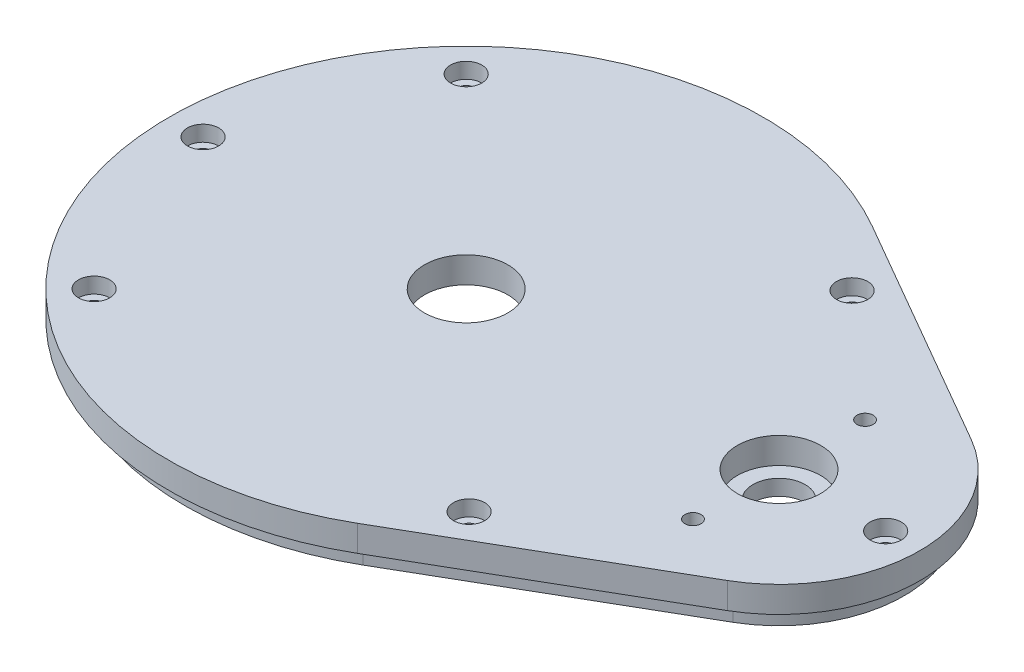
SolidWorks part; units mm, degrees
ref_plane "Front Plane" through (0, 0, 0) normal (0, 0, 1) x (1, 0, 0)
ref_plane "Top Plane" through (0, 0, 0) normal (0, 1, 0) x (1, 0, 0)
ref_plane "Right Plane" through (0, 0, 0) normal (1, 0, 0) x (0, 0, -1)
sketch "Sketch1" plane through (0, 0, 0) normal (0, 1, 0) x (1, 0, 0)
  line L8 (45, -16.5) -> (45, 16.5) construction
  line L9 (13.5, -49.3634) -> (58.5, -23.3827)
  line L10 (13.5, 49.3634) -> (58.5, 23.3827)
  circle A0 centre (-15, 0) radius 46.5 construction
  circle A1 centre (45, 0) radius 16.5 construction
  circle A2 centre (-15, 0) radius 8
  circle A3 centre (45, 0) radius 8
  circle A4 centre (45, 16.5) radius 1.55
  circle A5 centre (45, -16.5) radius 1.55
  circle A8 centre (-15, 0) radius 57 construction
  circle A9 centre (45, 0) radius 27 construction
  arc A12 (13.5, 49.3634) -> (13.5, -49.3634) centre (-15, 0) ccw
  arc A13 (58.5, 23.3827) -> (58.5, -23.3827) centre (45, 0) cw
  point P0 (0, 0)
  point P17 (45, 0)
  point P18 (45, 0)
extrude "Boss-Extrude1" add sketch "Sketch1" along normal blind 5
sketch "Sketch2" plane through (0, 0, 0) normal (0, -1, 0) x (1, 0, 0)
  circle A0 centre (45, 0) radius 5
  circle A1 centre (45, 0) radius 12
extrude "Boss-Extrude2" add sketch "Sketch2" along normal blind 3
sketch "Sketch4" plane through (0, 0, 0) normal (0, -1, 0) x (1, 0, 0)
  line L0 (12, 46.7654) -> (57, 20.7846)
  line L1 (12, -46.7654) -> (57, -20.7846)
  line L3 (11, -45.0333) -> (56, -19.0526)
  line L4 (11, 45.0333) -> (56, 19.0526)
  circle A0 centre (-15, 0) radius 54 construction
  circle A1 centre (45, 0) radius 24 construction
  arc A2 (12, 46.7654) -> (12, -46.7654) centre (-15, 0) ccw
  arc A3 (57, 20.7846) -> (57, -20.7846) centre (45, 0) cw
  circle A4 centre (-15, 0) radius 52 construction
  circle A5 centre (45, 0) radius 22 construction
  arc A8 (56, -19.0526) -> (56, 19.0526) centre (45, 0) ccw
  arc A9 (11, -45.0333) -> (11, 45.0333) centre (-15, 0) cw
extrude "Boss-Extrude3" add sketch "Sketch4" along normal blind 4
sketch "Sketch5" plane through (0, 5, 0) normal (0, 1, 0) x (1, 0, 0)
  line L0 (-67, 0) -> (-65.45, 0) construction
  line L1 (67, 0) -> (65.45, 0) construction
  line L2 (-51.9706, -36.9706) -> (21.9706, 36.9706) construction
  line L3 (-15, 0) -> (-51.7696, 36.7696) construction
  line L4 (-51.7696, -36.7696) -> (-50.6735, -35.6735) construction
  line L5 (23.0666, -38.0666) -> (22.2916, -36.7243) construction
  line L6 (11, 45.0333) -> (56, 19.0526) construction
  line L7 (-51.7696, 36.7696) -> (-50.6735, 35.6735) construction
  line L8 (11, -45.0333) -> (56, -19.0526) construction
  line L9 (-15, 0) -> (22.2847, 36.7283) construction
  line L10 (23.0666, 38.0666) -> (22.2847, 36.7283) construction
  line L11 (-15, 0) -> (45, 0) construction
  arc A17 (11, 45.0333) -> (11, -45.0333) centre (-15, 0) ccw construction
  circle A18 centre (-65.45, 0) radius 1.55
  arc A20 (56, -19.0526) -> (56, 19.0526) centre (45, 0) ccw construction
  circle A21 centre (65.45, 0) radius 1.55
  circle A29 centre (-50.6735, -35.6735) radius 1.55
  circle A33 centre (22.2847, 36.7283) radius 1.55
  circle A35 centre (22.2916, -36.7243) radius 1.55
  circle A36 centre (-50.6735, 35.6735) radius 1.55
  point P39 (-15, 0)
extrude "Cut-Extrude1" cut sketch "Sketch5" against normal blind 5
sketch "Sketch6" plane through (0, 5, 0) normal (0, 1, 0) x (1, 0, 0)
  circle A0 centre (-50.6735, 35.6735) radius 3
  circle A1 centre (-65.45, 0) radius 3
  circle A2 centre (-50.6735, -35.6735) radius 3
  circle A3 centre (22.2916, -36.7243) radius 3
  circle A4 centre (22.2847, 36.7283) radius 3
  circle A5 centre (65.45, 0) radius 3
extrude "Cut-Extrude2" cut sketch "Sketch6" against normal blind 3
